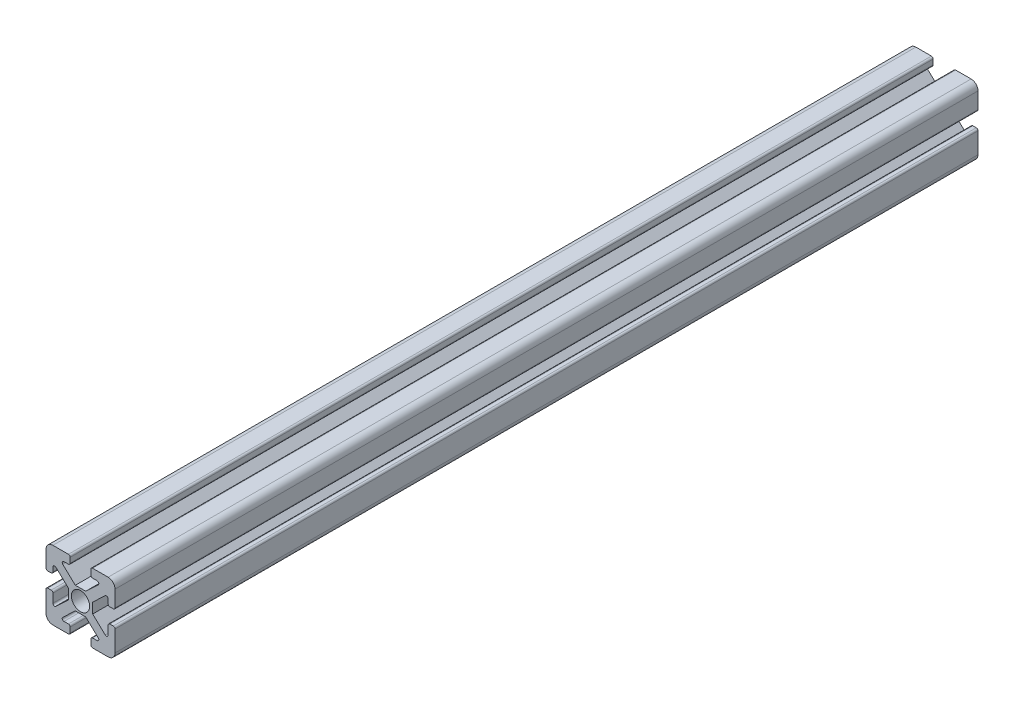
SolidWorks part; units mm, degrees
ref_plane "Front Plane" through (0, 0, 0) normal (0, 0, 1) x (1, 0, 0)
ref_plane "Top Plane" through (0, 0, 0) normal (0, 1, 0) x (1, 0, 0)
ref_plane "Right Plane" through (0, 0, 0) normal (1, 0, 0) x (0, 0, -1)
sketch "Sketch1" plane through (0, 0, 0) normal (0, 0, 1) x (1, 0, 0)
  line L0 (0, 2) -> (0, 8.0075)
  line L1 (2, 20) -> (6.5, 20)
  line L2 (20, 18) -> (20, 13.3075)
  line L3 (18, 0) -> (13.5, 0)
  line L4 (10, 0.2965) -> (10, 6.7965) construction
  line L5 (-0.015, 9.9158) -> (6.485, 9.9158) construction
  line L6 (18.5, 8.5075) -> (19.5, 8.5075)
  line L7 (18.5, 12.8075) -> (19.5, 12.8075)
  line L8 (13, 19.5) -> (13, 18.0175)
  line L9 (7, 19.5) -> (7, 18.0175)
  line L10 (2, 14.5732) -> (2, 13.3075)
  line L11 (5.2, 2.5071) -> (6.5, 2.5071)
  line L12 (18, 5.4513) -> (18, 8.0075)
  line L13 (14.8, 17.5175) -> (13.5, 17.5175)
  line L14 (1.5, 12.8075) -> (0.5, 12.8075)
  line L15 (13.5, 20) -> (18, 20)
  line L16 (6.5, 17.5175) -> (5.2, 17.5175)
  line L17 (20, 8.0075) -> (20, 2)
  line L18 (18, 13.3075) -> (18, 14.5732)
  line L19 (0, 13.3075) -> (0, 18)
  line L20 (2, 8.0075) -> (2, 5.4513)
  line L21 (6.5, 0) -> (2, 0)
  line L22 (13.5, 2.5071) -> (14.8, 2.5071)
  line L23 (1.5, 8.5075) -> (0.5, 8.5075)
  line L24 (13, 0.5) -> (13, 2.0071)
  line L25 (7, 2.0071) -> (7, 0.5)
  line L26 (17.1575, 14.9375) -> (13.515, 11.5123)
  line L27 (15.1425, 16.6533) -> (11.5, 13.228)
  line L28 (4.8575, 16.6533) -> (8.5, 13.228)
  line L29 (2.8425, 14.9375) -> (6.485, 11.5123)
  line L30 (13.515, 8.5123) -> (17.1575, 5.0871)
  line L31 (8.5, 6.7965) -> (11.5, 6.7965)
  line L32 (6.485, 8.5123) -> (6.485, 11.5123)
  line L33 (8.5, 13.228) -> (11.5, 13.228)
  line L34 (13.515, 8.5123) -> (13.515, 11.5123)
  line L37 (6.485, 8.5123) -> (2.8425, 5.0871)
  line L38 (13.515, 9.9158) -> (19.985, 9.9158) construction
  line L39 (11.5, 6.7965) -> (15.1425, 3.3713)
  line L41 (8.5, 6.7965) -> (4.8575, 3.3713)
  line L43 (10.0737, 13.228) -> (10.0737, 19.728) construction
  circle A0 centre (10, 10) radius 2.65
  arc A1 (0, 18) -> (2, 20) centre (2, 18) cw
  arc A2 (0, 2) -> (2, 0) centre (2, 2) ccw
  arc A3 (20, 2) -> (18, 0) centre (18, 2) cw
  arc A4 (18, 20) -> (20, 18) centre (18, 18) cw
  arc A5 (19.5, 8.5075) -> (20, 8.0075) centre (19.5, 8.0075) cw
  arc A6 (0.5, 8.5075) -> (0, 8.0075) centre (0.5, 8.0075) ccw
  arc A7 (0.5, 12.8075) -> (0, 13.3075) centre (0.5, 13.3075) cw
  arc A8 (13, 19.5) -> (13.5, 20) centre (13.5, 19.5) cw
  arc A9 (7, 19.5) -> (6.5, 20) centre (6.5, 19.5) ccw
  arc A10 (18, 8.0075) -> (18.5, 8.5075) centre (18.5, 8.0075) cw
  arc A11 (18.5, 12.8075) -> (18, 13.3075) centre (18.5, 13.3075) cw
  arc A12 (19.5, 12.8075) -> (20, 13.3075) centre (19.5, 13.3075) ccw
  arc A13 (7, 18.0175) -> (6.5, 17.5175) centre (6.5, 18.0175) cw
  arc A14 (13.5, 17.5175) -> (13, 18.0175) centre (13.5, 18.0175) cw
  arc A15 (2, 13.3075) -> (1.5, 12.8075) centre (1.5, 13.3075) cw
  arc A16 (2, 8.0075) -> (1.5, 8.5075) centre (1.5, 8.0075) ccw
  arc A17 (6.5, 2.5071) -> (7, 2.0071) centre (6.5, 2.0071) cw
  arc A18 (7, 0.5) -> (6.5, 0) centre (6.5, 0.5) cw
  arc A19 (13.5, 2.5071) -> (13, 2.0071) centre (13.5, 2.0071) ccw
  arc A20 (13, 0.5) -> (13.5, 0) centre (13.5, 0.5) ccw
  arc A21 (17.1575, 5.0871) -> (18, 5.4513) centre (17.5, 5.4513) ccw
  arc A22 (14.8, 2.5071) -> (15.1425, 3.3713) centre (14.8, 3.0071) ccw
  arc A23 (5.2, 2.5071) -> (4.8575, 3.3713) centre (5.2, 3.0071) cw
  arc A24 (2, 5.4513) -> (2.8425, 5.0871) centre (2.5, 5.4513) ccw
  arc A25 (2, 14.5732) -> (2.8425, 14.9375) centre (2.5, 14.5732) cw
  arc A26 (4.8575, 16.6533) -> (5.2, 17.5175) centre (5.2, 17.0175) cw
  arc A27 (17.1575, 14.9375) -> (18, 14.5732) centre (17.5, 14.5732) cw
  arc A28 (14.8, 17.5175) -> (15.1425, 16.6533) centre (14.8, 17.0175) cw
  dimension "D3" = 2
  dimension "D8" = 0.5
  dimension "D4" = 0.5
  dimension "D5" = 0.5
  dimension "D6" = 0.5
  dimension "D7" = 0.5
  dimension "D9" = 5.3
  dimension "D12" = 2
  dimension "D13" = 5
  dimension "D14" = 1.3
  dimension "D10" = 3
  dimension "D11" = 2
  dimension "D15" = 1.3
  dimension "D16" = 1.3
  dimension "D17" = 6
  dimension "D18" = 5.3
  dimension "D19" = 10
  dimension "D20" = 10
  dimension "D21" = 133.239
extrude "Boss-Extrude1" add sketch "Sketch1" along normal blind 250
